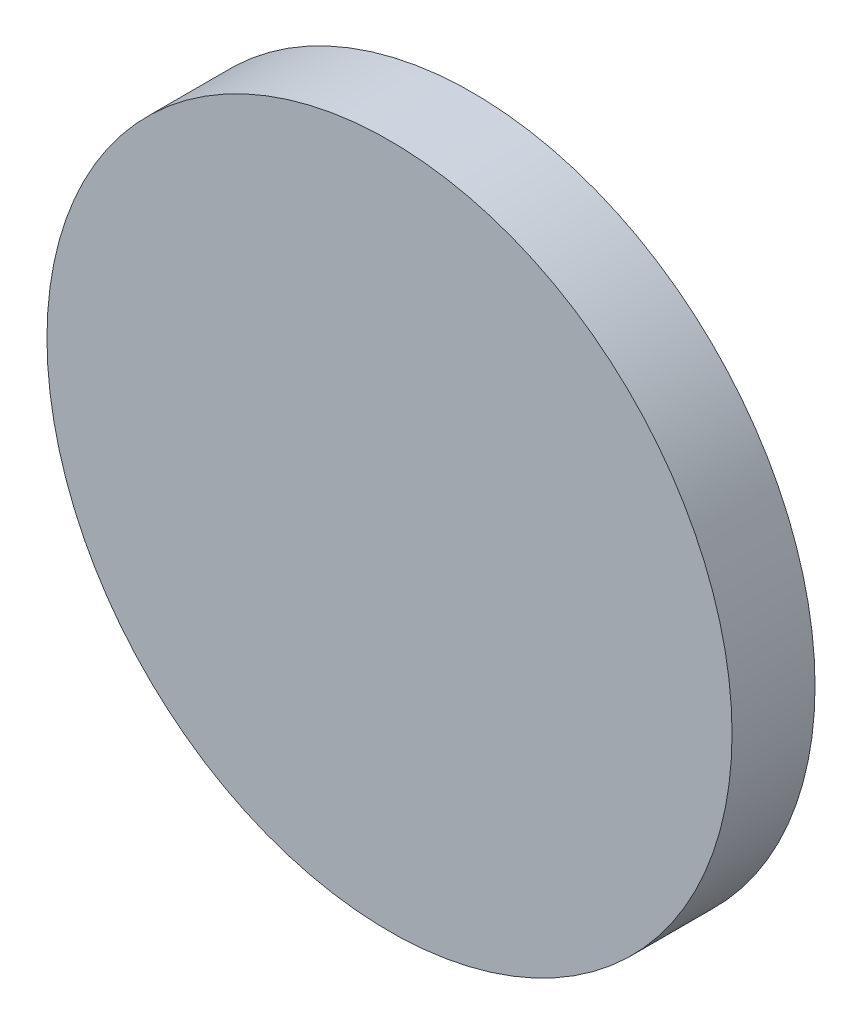
SolidWorks part; units mm, degrees
ref_plane "Front Plane" through (0, 0, 0) normal (0, 0, 1) x (1, 0, 0)
ref_plane "Top Plane" through (0, 0, 0) normal (0, 1, 0) x (1, 0, 0)
ref_plane "Right Plane" through (0, 0, 0) normal (1, 0, 0) x (0, 0, -1)
sketch "Sketch2" plane through (0, 0, 0) normal (0, 0, 1) x (1, 0, 0)
  circle A0 centre (0, -1.3364) radius 82.55
  dimension "D1" = 165.1
extrude "Boss-Extrude1" add sketch "Sketch2" along normal blind 20
